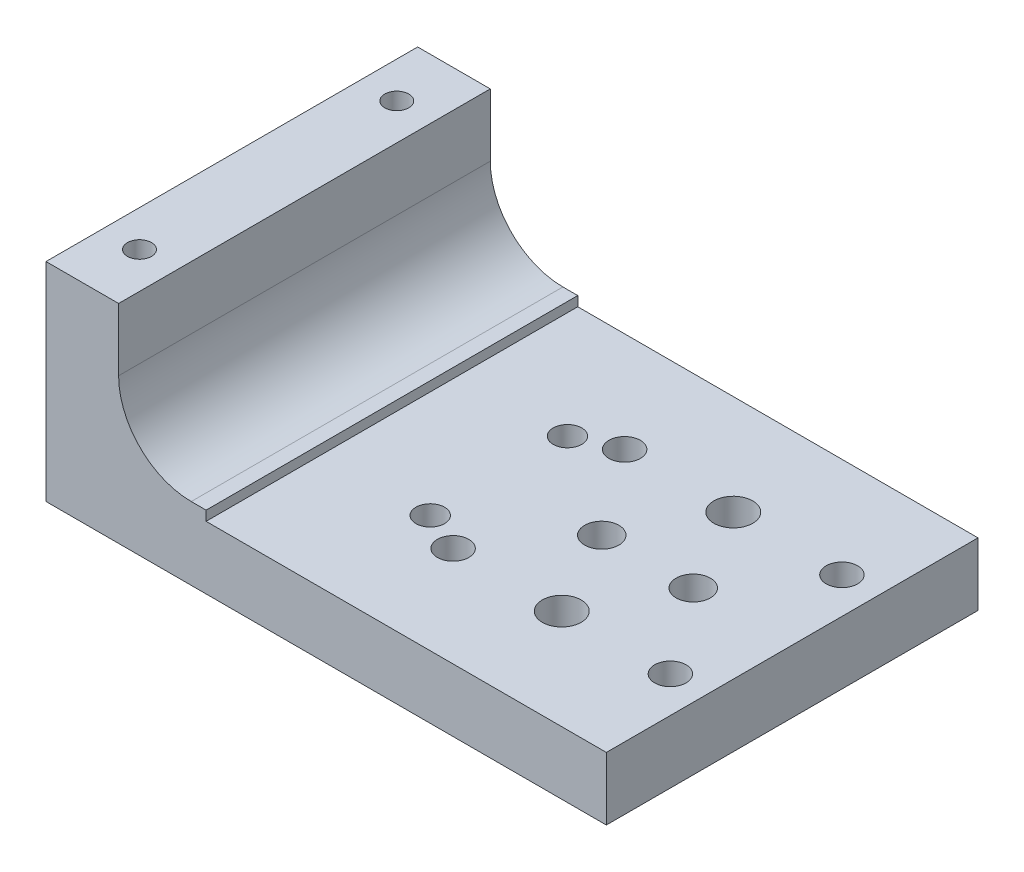
SolidWorks part; units mm, degrees
material "6061-T6 ALUMINUM"
ref_plane "Front/Back" through (0, 0, 0) normal (0, 0, 1) x (1, 0, 0)
ref_plane "Top/Bottom" through (0, 0, 0) normal (0, 1, 0) x (1, 0, 0)
ref_plane "Right/Left" through (0, 0, 0) normal (1, 0, 0) x (0, 0, -1)
sketch "Sketch1" plane through (0, 0, 0) normal (0, 0, 1) x (1, 0, 0)
  line L0 (0, 0) -> (98, 0)
  line L1 (0, 0) -> (0, 36.35)
  line L2 (0, 36.35) -> (12.7, 36.35)
  line L3 (12.7, 36.35) -> (12.7, 25.4)
  line L4 (25.4, 12.7) -> (98, 12.7)
  line L5 (98, 12.7) -> (98, 0)
  arc A0 (12.7, 25.4) -> (25.4, 12.7) centre (25.4, 25.4) ccw
  dimension "D1" = 12.7
  dimension "D2" = 12.7
  dimension "D3" = 36.35
  dimension "D4" = 98
extrude "Extrude1" add sketch "Sketch1" along normal mid plane 65
sketch "Sketch2" plane through (0, 0, -32.5) normal (0, 0, -1) x (-1, 0, 0)
  line L0 (0, 0) -> (-98, 0) construction
  line L1 (-98, 12.7) -> (-28, 12.7)
  line L2 (-98, 12.7) -> (-98, 11)
  line L3 (-98, 11) -> (-28, 11)
  line L4 (-28, 12.7) -> (-28, 11)
  dimension "D1" = 70
  dimension "D2" = 11
extrude "Cut-Extrude1" cut sketch "Sketch2" against normal through all
hole_wizard "M5 Clearance Hole1" positions "Sketch4" profile "Sketch3" hole size "M5" standard "_*ATS Preferred Ansi METRIC" end condition through all
sketch "Sketch4" plane through (0, 0, 0) normal (0, -1, 0) x (1, 0, 0)
  point P0 (53.7, 15)
  point P1 (91.7, 15)
  point P4 (91.7, -15)
  point P7 (53.7, -15)
sketch "Sketch3" plane through (53.7, 0, 15) normal (1, 0, 0) x (0, 0, -1)
  line L0 (0, 0) -> (0, 36.35)
  line L1 (0, 36.35) -> (2.75, 36.35)
  line L2 (2.75, 36.35) -> (2.75, 0)
  line L5 (2.75, 0) -> (0, 0)
  line L11 (0, -6.35) -> (0, 107.95) construction
  dimension "Thru Hole Dia." = 5.5
  dimension "Thru Hole Depth" = 36.35
hole_wizard "M5x0.8 Tapped Hole1" positions "Sketch6" profile "Sketch5" tap size "M5x0.8" standard "_*ATS Preferred Ansi METRIC"
sketch "Sketch6" plane through (0, 36.35, 0) normal (0, 1, 0) x (-1, 0, 0)
  line L0 (0, 0) -> (-12.7, 0) construction
  line L1 (-12.7, 32.5) -> (-12.7, -32.5) construction
  line L4 (-6.35, 0) -> (-6.35, 14.0998) construction
  point P0 (-6.35, 22.5)
  point P1 (-6.35, -22.5)
  dimension "D1" = 45
sketch "Sketch5" plane through (6.35, 36.35, 22.5) normal (1, 0, 0) x (0, 0, 1)
  line L0 (0, 0) -> (0, 20.3118)
  line L1 (0, 20.3118) -> (2.1, 19.05)
  line L2 (2.1, 19.05) -> (2.1, 0)
  line L5 (2.1, 0) -> (0, 0)
  line L10 (0, 20.3118) -> (-2.1, 19.05) construction
  line L11 (0, -6.35) -> (0, 107.95) construction
  dimension "Tap Drill Dia." = 4.2
  dimension "Tap Drill Depth" = 19.05
  dimension "Drill Angle" = 118
cosmetic thread "Hole Thread1"
cosmetic thread "Hole Thread2"
hole_wizard "Ø5.0 (5) Diameter Hole1" positions "Sketch8" profile "Sketch7" hole size "Ø5.0" standard "Ansi Metric" end condition through all
sketch "Sketch8" plane through (0, 0, 0) normal (0, -1, 0) x (1, 0, 0)
  line L0 (50.2, 24) -> (59.2, 24) construction
  line L1 (50.2, -24) -> (59.2, -24) construction
  line L2 (49.2, -24) -> (49.2, 24) construction
  point P0 (46.7, 12)
  point P1 (46.7, -12)
  dimension "D1" = 12
  dimension "D2" = 12
  dimension "D3" = 2.5
sketch "Sketch7" plane through (46.7, 0, 12) normal (1, 0, 0) x (0, 0, -1)
  line L0 (0, 0) -> (0, 36.35)
  line L1 (0, 36.35) -> (2.5, 36.35)
  line L2 (2.5, 36.35) -> (2.5, 0)
  line L5 (2.5, 0) -> (0, 0)
  line L11 (0, -6.35) -> (0, 107.95) construction
  dimension "Thru Hole Dia." = 5
  dimension "Thru Hole Depth" = 36.35
hole_wizard "M8x1.25 Tapped Hole1" positions "Sketch10" profile "Sketch9" tap size "M8x1.25" standard "_*ATS Preferred Ansi METRIC" end condition through all
sketch "Sketch10" plane through (0, 0, 0) normal (0, -1, 0) x (1, 0, 0)
  line L0 (91.7, -15) -> (53.7, -15) construction
  line L6 (91.7, 15) -> (53.7, 15) construction
  point P0 (72.7, -15)
  point P1 (72.7, 15)
sketch "Sketch9" plane through (72.7, 0, -15) normal (1, 0, 0) x (0, 0, -1)
  line L0 (0, 0) -> (0, 36.35)
  line L1 (0, 36.35) -> (3.4, 36.35)
  line L2 (3.4, 36.35) -> (3.4, 0)
  line L5 (3.4, 0) -> (0, 0)
  line L11 (0, -6.35) -> (0, 107.95) construction
  dimension "Thru Tap Drill Dia." = 6.8
  dimension "Thru Tap Drill Depth" = 36.35
cosmetic thread "Hole Thread3"
cosmetic thread "Hole Thread4"
hole_wizard "Ø6.0 (6) Diameter Hole1" positions "Sketch12" profile "Sketch11" hole size "Ø6.0" standard "Ansi Metric" end condition through all
sketch "Sketch12" plane through (0, 0, 0) normal (0, -1, 0) x (1, 0, 0)
  line L0 (72.7, -15) -> (72.7, 15) construction
  line L3 (72.7, 0) -> (77.7891, 0) construction
  point P0 (64.7, 0)
  point P1 (80.7, 0)
  dimension "D1" = 16
sketch "Sketch11" plane through (64.7, 0, 0) normal (1, 0, 0) x (0, 0, -1)
  line L0 (0, 0) -> (0, 36.35)
  line L1 (0, 36.35) -> (3, 36.35)
  line L2 (3, 36.35) -> (3, 0)
  line L5 (3, 0) -> (0, 0)
  line L11 (0, -6.35) -> (0, 107.95) construction
  dimension "Thru Hole Dia." = 6
  dimension "Thru Hole Depth" = 36.35
